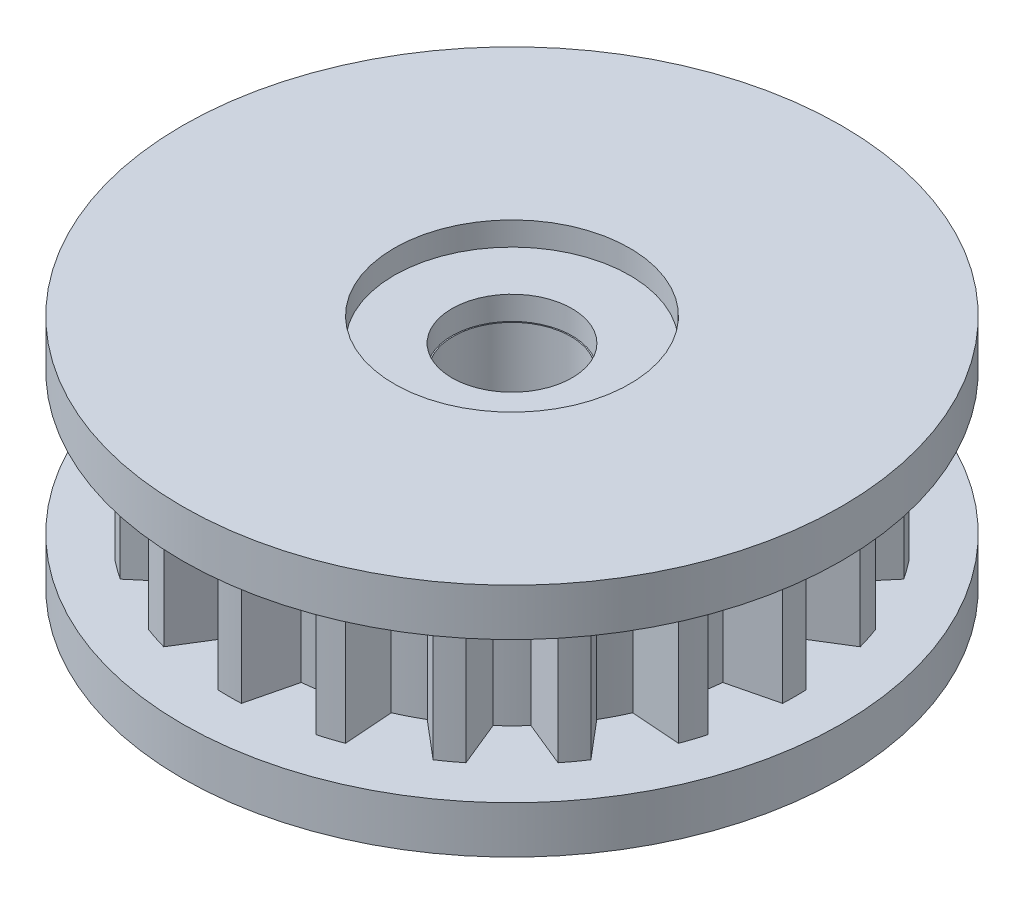
SolidWorks part; units mm, degrees
ref_plane "Front Plane" through (0, 0, 0) normal (0, 0, 1) x (1, 0, 0)
ref_plane "Top Plane" through (0, 0, 0) normal (0, 1, 0) x (1, 0, 0)
ref_plane "Right Plane" through (0, 0, 0) normal (1, 0, 0) x (0, 0, -1)
sketch "Sketch1" plane through (0, 0, 0) normal (0, 1, 0) x (1, 0, 0)
  line L0 (0, -12) -> (0, 12) construction
  line L1 (0.5, 11.9896) -> (1, 9.9499)
  line L2 (-0.5, 11.9896) -> (-1, 9.9499)
  line L3 (4.1805, 11.2483) -> (4.0257, 9.1539)
  line L4 (3.2295, 11.5573) -> (2.1236, 9.7719)
  line L5 (7.4518, 9.4059) -> (6.6574, 7.4618)
  line L6 (6.6428, 9.9937) -> (5.0394, 8.6374)
  line L7 (9.9937, 6.6428) -> (8.6374, 5.0394)
  line L8 (9.4059, 7.4518) -> (7.4618, 6.6574)
  line L9 (11.5573, 3.2295) -> (9.7719, 2.1236)
  line L10 (11.2483, 4.1805) -> (9.1539, 4.0257)
  line L11 (11.9896, -0.5) -> (9.9499, -1)
  line L12 (11.9896, 0.5) -> (9.9499, 1)
  line L13 (11.2483, -4.1805) -> (9.1539, -4.0257)
  line L14 (11.5573, -3.2295) -> (9.7719, -2.1236)
  line L15 (9.4059, -7.4518) -> (7.4618, -6.6574)
  line L16 (9.9937, -6.6428) -> (8.6374, -5.0394)
  line L17 (6.6428, -9.9937) -> (5.0394, -8.6374)
  line L18 (7.4518, -9.4059) -> (6.6574, -7.4618)
  line L19 (3.2295, -11.5573) -> (2.1236, -9.7719)
  line L20 (4.1805, -11.2483) -> (4.0257, -9.1539)
  line L21 (-0.5, -11.9896) -> (-1, -9.9499)
  line L22 (0.5, -11.9896) -> (1, -9.9499)
  line L23 (-4.1805, -11.2483) -> (-4.0257, -9.1539)
  line L24 (-3.2295, -11.5573) -> (-2.1236, -9.7719)
  line L25 (-7.4518, -9.4059) -> (-6.6574, -7.4618)
  line L26 (-6.6428, -9.9937) -> (-5.0394, -8.6374)
  line L27 (-9.9937, -6.6428) -> (-8.6374, -5.0394)
  line L28 (-9.4059, -7.4518) -> (-7.4618, -6.6574)
  line L29 (-11.5573, -3.2295) -> (-9.7719, -2.1236)
  line L30 (-11.2483, -4.1805) -> (-9.1539, -4.0257)
  line L31 (-11.9896, 0.5) -> (-9.9499, 1)
  line L32 (-11.9896, -0.5) -> (-9.9499, -1)
  line L33 (-11.2483, 4.1805) -> (-9.1539, 4.0257)
  line L34 (-11.5573, 3.2295) -> (-9.7719, 2.1236)
  line L35 (-9.4059, 7.4518) -> (-7.4618, 6.6574)
  line L36 (-9.9937, 6.6428) -> (-8.6374, 5.0394)
  line L37 (-6.6428, 9.9937) -> (-5.0394, 8.6374)
  line L38 (-7.4518, 9.4059) -> (-6.6574, 7.4618)
  line L39 (-3.2295, 11.5573) -> (-2.1236, 9.7719)
  line L40 (-4.1805, 11.2483) -> (-4.0257, 9.1539)
  circle A0 centre (0, 0) radius 2.5
  circle A1 centre (0, 0) radius 12 construction
  circle A2 centre (0, 0) radius 10 construction
  arc A4 (0.5, 11.9896) -> (-0.5, 11.9896) centre (0, 0) ccw
  arc A6 (4.1805, 11.2483) -> (3.2295, 11.5573) centre (0, 0) ccw
  arc A8 (7.4518, 9.4059) -> (6.6428, 9.9937) centre (0, 0) ccw
  arc A10 (9.9937, 6.6428) -> (9.4059, 7.4518) centre (0, 0) ccw
  arc A12 (11.5573, 3.2295) -> (11.2483, 4.1805) centre (0, 0) ccw
  arc A14 (11.9896, -0.5) -> (11.9896, 0.5) centre (0, 0) ccw
  arc A16 (11.2483, -4.1805) -> (11.5573, -3.2295) centre (0, 0) ccw
  arc A18 (9.4059, -7.4518) -> (9.9937, -6.6428) centre (0, 0) ccw
  arc A20 (6.6428, -9.9937) -> (7.4518, -9.4059) centre (0, 0) ccw
  arc A22 (3.2295, -11.5573) -> (4.1805, -11.2483) centre (0, 0) ccw
  arc A24 (-0.5, -11.9896) -> (0.5, -11.9896) centre (0, 0) ccw
  arc A26 (-4.1805, -11.2483) -> (-3.2295, -11.5573) centre (0, 0) ccw
  arc A28 (-7.4518, -9.4059) -> (-6.6428, -9.9937) centre (0, 0) ccw
  arc A30 (-9.9937, -6.6428) -> (-9.4059, -7.4518) centre (0, 0) ccw
  arc A32 (-11.5573, -3.2295) -> (-11.2483, -4.1805) centre (0, 0) ccw
  arc A34 (-11.9896, 0.5) -> (-11.9896, -0.5) centre (0, 0) ccw
  arc A36 (-11.2483, 4.1805) -> (-11.5573, 3.2295) centre (0, 0) ccw
  arc A38 (-9.4059, 7.4518) -> (-9.9937, 6.6428) centre (0, 0) ccw
  arc A40 (-6.6428, 9.9937) -> (-7.4518, 9.4059) centre (0, 0) ccw
  arc A42 (-3.2295, 11.5573) -> (-4.1805, 11.2483) centre (0, 0) ccw
  arc A62 (-1, 9.9499) -> (-2.1236, 9.7719) centre (0, 0) ccw
  arc A63 (5.0394, 8.6374) -> (4.0257, 9.1539) centre (0, 0) ccw
  arc A64 (2.1236, 9.7719) -> (1, 9.9499) centre (0, 0) ccw
  arc A65 (7.4618, 6.6574) -> (6.6574, 7.4618) centre (0, 0) ccw
  arc A66 (9.1539, 4.0257) -> (8.6374, 5.0394) centre (0, 0) ccw
  arc A67 (9.9499, 1) -> (9.7719, 2.1236) centre (0, 0) ccw
  arc A68 (9.7719, -2.1236) -> (9.9499, -1) centre (0, 0) ccw
  arc A69 (8.6374, -5.0394) -> (9.1539, -4.0257) centre (0, 0) ccw
  arc A70 (6.6574, -7.4618) -> (7.4618, -6.6574) centre (0, 0) ccw
  arc A71 (4.0257, -9.1539) -> (5.0394, -8.6374) centre (0, 0) ccw
  arc A72 (1, -9.9499) -> (2.1236, -9.7719) centre (0, 0) ccw
  arc A73 (-2.1236, -9.7719) -> (-1, -9.9499) centre (0, 0) ccw
  arc A74 (-5.0394, -8.6374) -> (-4.0257, -9.1539) centre (0, 0) ccw
  arc A75 (-7.4618, -6.6574) -> (-6.6574, -7.4618) centre (0, 0) ccw
  arc A76 (-9.1539, -4.0257) -> (-8.6374, -5.0394) centre (0, 0) ccw
  arc A77 (-9.9499, -1) -> (-9.7719, -2.1236) centre (0, 0) ccw
  arc A78 (-9.7719, 2.1236) -> (-9.9499, 1) centre (0, 0) ccw
  arc A79 (-8.6374, 5.0394) -> (-9.1539, 4.0257) centre (0, 0) ccw
  arc A80 (-6.6574, 7.4618) -> (-7.4618, 6.6574) centre (0, 0) ccw
  arc A81 (-4.0257, 9.1539) -> (-5.0394, 8.6374) centre (0, 0) ccw
  point P89 (0, 0)
  dimension "D1" = 5
  dimension "D2" = 24
  dimension "D3" = 20
  dimension "D4" = 0.5
  dimension "D5" = 1
  dimension "D6" = 20
extrude "Boss-Extrude1" add sketch "Sketch1" along normal blind 6
sketch "Sketch2" plane through (0, 0, 0) normal (0, 0, 1) x (1, 0, 0)
  line L0 (0, -1000) -> (0, 49000) construction
  line L1 (0.5, 6) -> (-0.5, 6) construction
  line L2 (0, 6) -> (14, 6) construction
  line L3 (0, 6) -> (0, 8) construction
  line L4 (0, 8) -> (14, 8) construction
  line L5 (14, 6) -> (14, 8) construction
  line L6 (-1011.9896, 3) -> (48988.0104, 3) construction
  line L7 (-11.9896, 6) -> (-11.9896, 0) construction
  line L8 (0, -2) -> (14, -2) construction
  line L9 (14, 0) -> (14, -2) construction
  line L10 (0, 0) -> (14, 0) construction
  line L11 (0, 0) -> (0, -2) construction
  line L12 (14, 0) -> (2.55, 0)
  line L13 (14, 8) -> (2.55, 8)
  line L14 (14, 8) -> (14, 6)
  line L15 (14, 6) -> (2.55, 6)
  line L16 (2.55, 8) -> (2.55, 6)
  line L17 (2.55, -2) -> (2.55, 0)
  line L18 (14, -2) -> (2.55, -2)
  line L19 (14, -2) -> (14, 0)
  point P14 (-11.9896, 3)
  dimension "D1" = 14
  dimension "D2" = 2
  dimension "D3" = 2.55
revolve "Revolve1" add sketch "Sketch2" angle 360 about L0
sketch "Sketch3" plane through (0, 8, 0) normal (0, 1, 0) x (1, 0, 0)
  circle A0 centre (0, 0) radius 5
  dimension "D1" = 10
extrude "Cut-Extrude1" cut sketch "Sketch3" against normal blind 1
